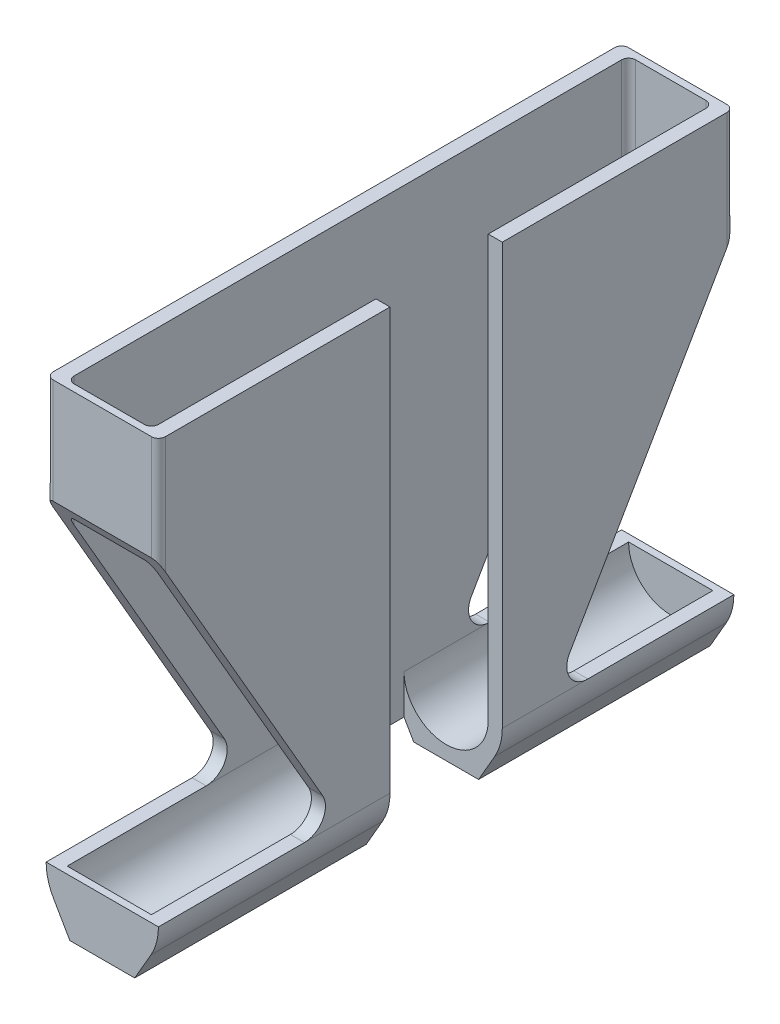
SolidWorks part; units mm, degrees
ref_plane "前视基准面" through (0, 0, 0) normal (0, 0, 1) x (1, 0, 0)
ref_plane "上视基准面" through (0, 0, 0) normal (0, 1, 0) x (1, 0, 0)
ref_plane "右视基准面" through (0, 0, 0) normal (1, 0, 0) x (0, 0, -1)
sketch "草图1" plane through (0, 0, 0) normal (0, 0, 1) x (1, 0, 0)
  line L0 (0, 0) -> (0, -60)
  line L1 (12, -60) -> (12, 0)
  line L2 (-2, 0) -> (-2, -60)
  line L3 (14, -60) -> (14, 0)
  line L4 (-2, 0) -> (0, 0)
  line L5 (12, 0) -> (14, 0)
  arc A0 (0, -60) -> (12, -60) centre (6, -60) ccw
  arc A1 (-2, -60) -> (14, -60) centre (6, -60) ccw
  dimension "D3" = 6
  dimension "D1" = 2
  dimension "D2" = 60
  dimension "D4" = 60
extrude "凸台-拉伸1" add sketch "草图1" along normal mid plane 80
sketch "草图3" plane through (0, 0, 40) normal (0, 0, 1) x (1, 0, 0)
  line L0 (14, -60) -> (14, 0) construction
  line L1 (-2, 0) -> (-2, -60) construction
  line L2 (14, -60) -> (14, 0)
  line L3 (-2, 0) -> (-2, -60)
  line L4 (-2, 0) -> (14, 0)
  arc A0 (-2, -60) -> (14, -60) centre (6, -60) ccw construction
  arc A1 (-2, -60) -> (14, -60) centre (6, -60) ccw
extrude "凸台-拉伸2" add sketch "草图3" along normal blind 1
mirror "镜向1" about plane through (0, 0, 0) normal (0, 0, 1) of "凸台-拉伸2"
sketch "草图4" plane through (-2, 0, 0) normal (-1, 0, 0) x (0, 0, 1)
  line L0 (0, 0) -> (0, -19.2867) construction
  line L1 (15, -60) -> (41, -60)
  line L2 (41, -60) -> (-41, -60) construction
  line L3 (41, -60) -> (41, -14.9667)
  line L4 (41, 0) -> (41, -60) construction
  line L5 (41, -14.9667) -> (15, -60)
  line L6 (-41, -14.9667) -> (-15, -60)
  line L7 (-41, -60) -> (-41, -14.9667)
  line L8 (-15, -60) -> (-41, -60)
  dimension "D1" = 60
  dimension "D2" = 30
extrude "切除-拉伸7" cut sketch "草图4" against normal up to surface (16 mm away) up to face at (14, -30, 0)
fillet "圆角1" radius 3 4 edges at (13, -60, -15) (-1, -60, -15) (-1, -60, 15) (13, -60, 15)
sketch "草图7" plane through (0, 0, 0) normal (0, 0, 1) x (1, 0, 0)
  line L0 (-0.9282, -64) -> (1.3812, -68)
  line L1 (1.3812, -68) -> (9.855, -68)
  line L2 (6, -60) -> (6, -55.2089) construction
  line L3 (10.6188, -68) -> (2.145, -68)
  line L4 (12.9282, -64) -> (10.6188, -68)
  line L5 (-0.9282, -64) -> (0.2554, -64)
  line L6 (11.7446, -64) -> (12.9282, -64)
  arc A0 (-2, -60) -> (14, -60) centre (6, -60) ccw construction
  arc A2 (0.2554, -64) -> (11.7446, -64) centre (6, -60) ccw
  dimension "D2" = 7
  dimension "D1" = 120
extrude "凸台-拉伸6" add sketch "草图7" along normal mid plane 82 contours A2 L5 L0 L1 L3 L4 L6
sketch "草图2" plane through (0, 0, 0) normal (0, 1, 0) x (1, 0, 0)
  line L0 (0, -8) -> (0, 8)
  line L1 (0, -20.1962) -> (0, 20.1962) construction
  line L2 (0, 8) -> (15.7637, 8)
  line L3 (15.7637, 8) -> (15.7637, -8)
  line L4 (15.7637, 0) -> (27.9019, 0) construction
  line L5 (0, -8) -> (15.7637, -8)
  point P10 (0, 0)
extrude "切除-拉伸1" cut sketch "草图2" against normal blind 80
fillet "圆角2" radius 1 8 edges at (14, -7.4833, 41) (-2, -7.4833, 41) (-2, -7.4833, -41) (14, -7.4833, -41) (12, -8.3494, -40) (12, -8.3494, 40) (0, -8.3494, 40) (0, -8.3494, -40)
